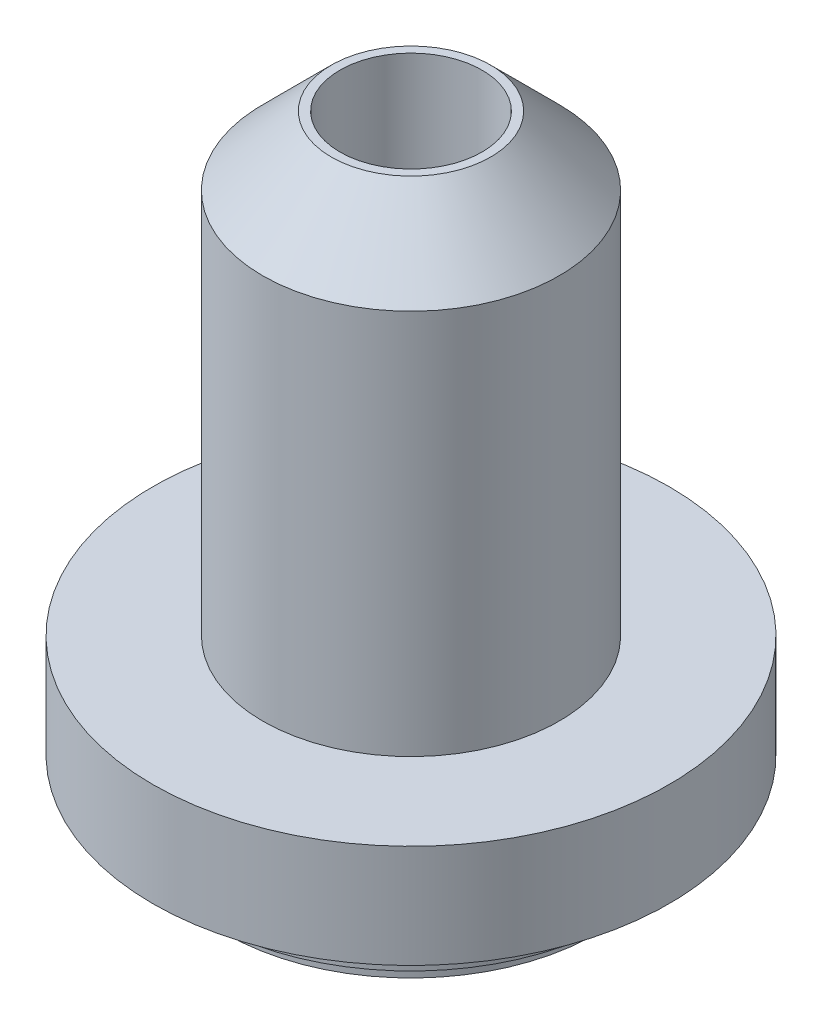
SolidWorks part; units mm, degrees
material "AISI 304"
ref_plane "Front Plane" through (0, 0, 0) normal (0, 0, 1) x (1, 0, 0)
ref_plane "Top Plane" through (0, 0, 0) normal (0, 1, 0) x (1, 0, 0)
ref_plane "Right Plane" through (0, 0, 0) normal (1, 0, 0) x (0, 0, -1)
sketch "Sketch1" plane through (0, 0, 0) normal (0, 1, 0) x (1, 0, 0)
  circle A0 centre (0, 0) radius 7.9375
  dimension "D1" = 15.875
extrude "Boss-Extrude1" add sketch "Sketch1" along normal blind 3.175
sketch "Sketch2" plane through (0, 0, 0) normal (0, -1, 0) x (1, 0, 0)
  circle A1 centre (0, 0) radius 6.35
  dimension "D1" = 12.7
extrude "Boss-Extrude2" add sketch "Sketch2" along normal blind 1.27
sketch "Sketch3" plane through (0, -1.27, 0) normal (0, -1, 0) x (1, 0, 0)
  circle A0 centre (0, 0) radius 5.715
  circle A1 centre (0, 0) radius 6.35 construction
  dimension "D1" = 0.635
extrude "Boss-Extrude3" add sketch "Sketch3" along normal blind 0.635
sketch "Sketch4" plane through (0, 3.175, 0) normal (0, 1, 0) x (1, 0, 0)
  circle A0 centre (0, 0) radius 4.5593
  dimension "D1" = 9.1186
extrude "Boss-Extrude4" add sketch "Sketch4" along normal blind 13.97
sketch "Sketch5" plane through (0, 17.145, 0) normal (0, 1, 0) x (1, 0, 0)
  circle A0 centre (0, 0) radius 2.4511
  circle A1 centre (0, 0) radius 10.1634
  dimension "D1" = 4.9022
extrude "Cut-Extrude1" cut sketch "Sketch5" against normal through all draft 45
sketch "Sketch6" plane through (0, 17.145, 0) normal (0, 1, 0) x (1, 0, 0)
  circle A0 centre (0, 0) radius 2.1844
  point P2 (0, 0)
  dimension "D1" = 4.3688
extrude "Cut-Extrude2" cut sketch "Sketch6" against normal through all
